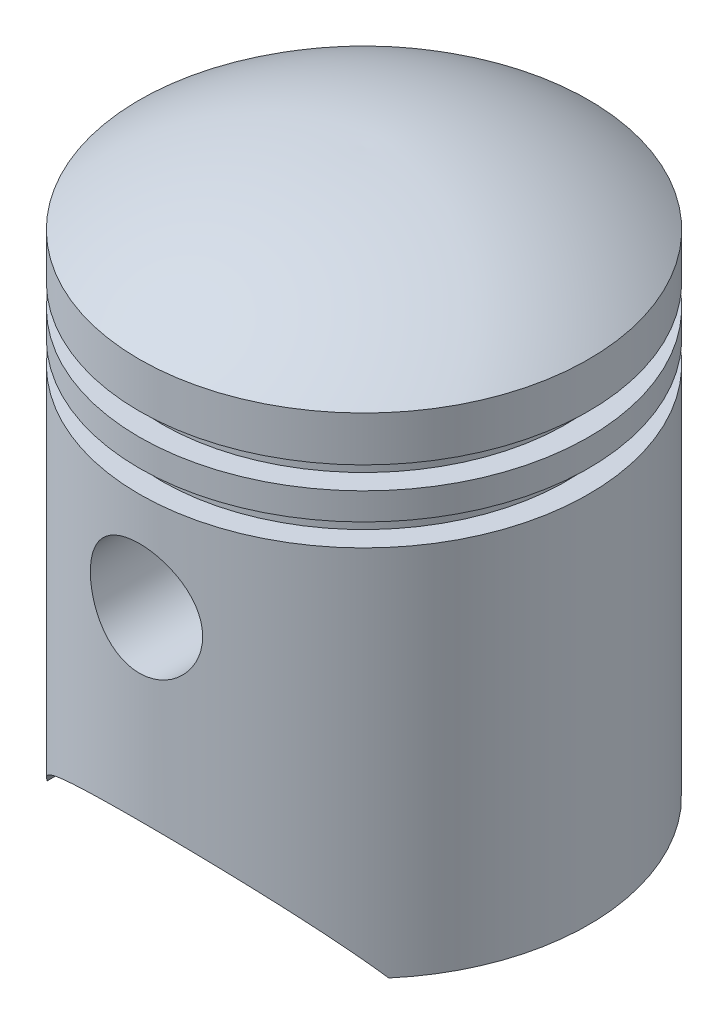
SolidWorks part; units mm, degrees
ref_plane "Front Plane" through (0, 0, 0) normal (0, 0, 1) x (1, 0, 0)
ref_plane "Top Plane" through (0, 0, 0) normal (0, 1, 0) x (1, 0, 0)
ref_plane "Right Plane" through (0, 0, 0) normal (1, 0, 0) x (0, 0, -1)
sketch "Sketch1" plane through (0, 0, 0) normal (0, 0, 1) x (1, 0, 0)
  line L0 (-13.9834, 26.3571) -> (-13.9834, 24.3565)
  line L1 (9.0166, -36.1429) -> (11.0166, -36.1429)
  line L3 (11.0166, 5.3571) -> (11.0166, -36.1429)
  line L4 (11.0166, 5.3571) -> (8.5166, 5.3571)
  line L5 (8.5166, 5.3571) -> (8.5166, 7.8571)
  line L6 (8.5166, 7.8571) -> (11.0166, 7.8571)
  line L7 (11.0166, 7.8571) -> (11.0166, 10.8571)
  line L8 (11.0166, 10.8571) -> (8.5166, 10.8571)
  line L9 (8.5166, 10.8571) -> (8.5166, 13.3571)
  line L10 (8.5166, 13.3571) -> (11.0166, 13.3571)
  line L11 (11.0166, 13.3571) -> (11.0166, 18.3571)
  line L12 (-13.9834, 26.3571) -> (-13.9834, -36.1429) construction
  line L13 (9.0166, 3.3571) -> (9.0166, -36.1429)
  line L14 (9.0166, 3.3571) -> (6.5166, 3.3571)
  line L15 (6.5166, 3.3571) -> (6.5166, 9.3571)
  line L16 (6.5166, 9.3571) -> (6.5166, 9.3571)
  line L17 (6.5166, 9.3571) -> (6.5166, 9.3571)
  line L18 (6.5166, 9.3571) -> (6.5166, 9.3571)
  line L19 (6.5166, 9.3571) -> (6.5166, 15.3571)
  line L20 (6.5166, 15.3571) -> (9.0166, 15.3571)
  line L21 (9.0166, 15.3571) -> (9.0166, 17.3417)
  line L22 (9.0166, 3.3571) -> (9.0166, -34.1429) construction
  line L23 (-11.9834, -34.1429) -> (9.0166, -34.1429) construction
  line L24 (-13.9834, -36.1429) -> (11.0166, -36.1429) construction
  line L25 (-11.9834, 24.3557) -> (-11.9834, -34.1429) construction
  arc A0 (11.0166, 18.3571) -> (-13.9834, 26.3571) centre (-12.9996, -13.6308) ccw
  arc A1 (9.0166, 17.3417) -> (-13.9834, 24.3565) centre (-12.9996, -13.6308) ccw
  arc A2 (9.0166, 17.3417) -> (-11.9834, 24.3557) centre (-12.9996, -13.6308) ccw construction
  dimension "D7" = 40
  dimension "D1" = 2.5
  dimension "D2" = 2.5
  dimension "D3" = 3
  dimension "D4" = 5
  dimension "D5" = 41.5
  dimension "D8" = 2
revolve "Revolve1" add sketch "Sketch1" angle 360 about L0
sketch "Sketch5" plane through (0, 0, 0) normal (0, 0, 1) x (1, 0, 0)
  line L0 (-38.9834, -36.1429) -> (11.0166, -36.1429) construction
  line L2 (-13.9834, -36.1429) -> (-13.9834, -26.1429) construction
  line L3 (5.0166, -36.1429) -> (-32.9834, -36.1429)
  arc A0 (5.0166, -36.1429) -> (-32.9834, -36.1429) centre (-13.9834, -49.1211) ccw
  point P5 (-13.9834, -36.1429)
  dimension "D1" = 10
  dimension "D2" = 38
extrude "Cut-Extrude1" cut sketch "Sketch5" against normal through all both and the other way through all
sketch "Sketch6" plane through (0, 0, 0) normal (0, 0, 1) x (1, 0, 0)
  line L0 (-13.9834, -26.1116) -> (-13.9834, 35.7326) construction
  arc A0 (5.0166, -36.1429) -> (-32.9834, -36.1429) centre (-13.9834, -49.1211) ccw construction
  circle A1 centre (-13.9834, -5.6429) radius 6.25
  dimension "D2" = 12.5
  dimension "D1" = 32
extrude "Cut-Extrude2" cut sketch "Sketch6" against normal through all both and the other way through all contours A1
ref_plane "Plane2" through (0, 0, 12) normal (0, 0, 1) x (1, 0, 0)
sketch "Sketch8" plane through (0, 0, 12) normal (0, 0, 1) x (1, 0, 0)
  circle A0 centre (-13.9834, -5.6429) radius 6.25 construction
  circle A1 centre (-13.9834, -5.6429) radius 6.25
  circle A2 centre (-13.9834, -5.6429) radius 7.25
  dimension "D1" = 14.5
extrude "Boss-Extrude1" add sketch "Sketch8" along normal up to next
mirror "Mirror1" about plane through (0, 0, 0) normal (0, 0, 1) of "Boss-Extrude1"
